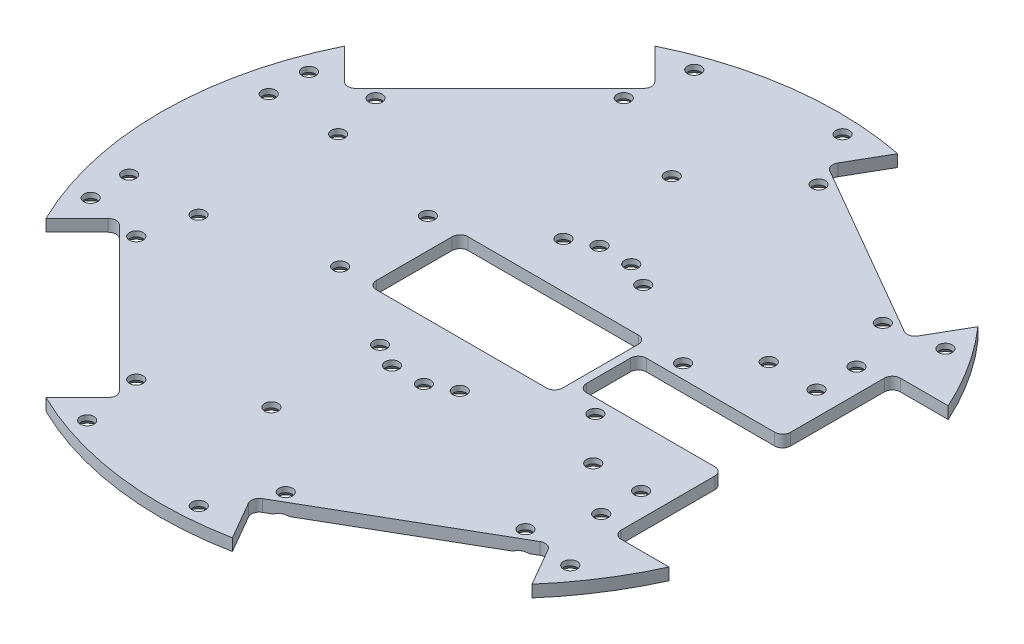
SolidWorks part; units mm, degrees
material "Liga 6061"
ref_plane "Plano frontal" through (0, 0, 0) normal (0, 0, 1) x (1, 0, 0)
ref_plane "Plano superior" through (0, 0, 0) normal (0, 1, 0) x (1, 0, 0)
ref_plane "Plano direito" through (0, 0, 0) normal (1, 0, 0) x (0, 0, -1)
sketch "Esboço1" plane through (0, 0, 0) normal (0, 1, 0) x (1, 0, 0)
  line L0 (0, -20.0389) -> (0, 0) construction
  line L1 (0, 0) -> (-50000, 0) construction
  line L2 (0, 0) -> (-35355.3391, -35355.3391) construction
  line L3 (-76.317, -37.4261) -> (-37.4261, -76.317) construction
  line L4 (16.3986, -83.4032) -> (64.03, -55.9032) construction
  line L5 (0, 0) -> (25000, -43301.2702) construction
  line L6 (16.3986, 83.4032) -> (64.03, 55.9032) construction
  line L7 (-76.317, 37.4261) -> (-37.4261, 76.317) construction
  line L8 (-61.1142, -30.0015) -> (-30.0015, -61.1142) construction
  line L9 (13.1617, -66.7968) -> (51.2668, -44.7968) construction
  line L10 (-67.1246, -28.2337) -> (-28.2337, -67.1246)
  line L15 (-67.1246, -28.2337) -> (-76.317, -37.4261)
  line L16 (-28.2337, -67.1246) -> (-37.4261, -76.317)
  line L17 (9.8986, -72.1448) -> (57.53, -44.6448)
  line L18 (64.03, -55.9032) -> (57.53, -44.6448)
  line L19 (16.3986, -83.4032) -> (9.8986, -72.1448)
  line L20 (64.03, 55.9032) -> (57.53, 44.6448)
  line L21 (9.8986, 72.1448) -> (57.53, 44.6448)
  line L22 (16.3986, 83.4032) -> (9.8986, 72.1448)
  line L23 (-28.2337, 67.1246) -> (-37.4261, 76.317)
  line L24 (-67.1246, 28.2337) -> (-28.2337, 67.1246)
  line L25 (-67.1246, 28.2337) -> (-76.317, 37.4261)
  line L28 (0, 0) -> (-75.1754, 27.3616) construction
  line L29 (-9.6973, 69) -> (0, 0) construction
  line L31 (0, 0) -> (64.7214, 47.0228) construction
  line L32 (3, 127.8652) -> (3, -125.0226) construction
  line L34 (0, 85) -> (0, 66.7968) construction
  arc A0 (-37.4261, -76.317) -> (16.3986, -83.4032) centre (0, 0) ccw
  arc A1 (64.03, -55.9032) -> (64.03, 55.9032) centre (0, 0) ccw
  arc A2 (-76.317, 37.4261) -> (-76.317, -37.4261) centre (0, 0) ccw
  arc A3 (16.3986, 83.4032) -> (-37.4261, 76.317) centre (0, 0) ccw
  circle A4 centre (-61.1142, -30.0015) radius 1.7
  circle A5 centre (-30.0015, -61.1142) radius 1.7
  circle A6 centre (13.1617, -66.7968) radius 1.7
  circle A7 centre (51.2668, -44.7968) radius 1.7
  circle A8 centre (-61.1142, 30.0015) radius 1.7
  circle A9 centre (-30.0015, 61.1142) radius 1.7
  circle A10 centre (13.1617, 66.7968) radius 1.7
  circle A11 centre (51.2668, 44.7968) radius 1.7
  circle A14 centre (-75.3985, 17.5) radius 1.5
  circle A15 centre (-58, 17.5) radius 1.5
  circle A16 centre (-58, -17.5) radius 1.5
  circle A17 centre (-75.3985, -17.5) radius 1.5
  circle A24 centre (-27.3176, 76.108) radius 1.5
  circle A32 centre (-75.1754, 27.3616) radius 1.5
  circle A33 centre (64.7214, 47.0228) radius 1.5
  circle A34 centre (64.7214, -47.0228) radius 1.5
  circle A35 centre (-75.1754, -27.3616) radius 1.5
  circle A36 centre (7, -26) radius 1.5
  circle A37 centre (13, -23) radius 1.5
  circle A38 centre (35, -11) radius 1.5
  circle A48 centre (5.2686, 80.7056) radius 1.5
  circle A49 centre (-7.0429, 50.1863) radius 1.5
  circle A50 centre (-27.3176, -76.108) radius 1.5
  circle A51 centre (5.2686, -80.7056) radius 1.5
  circle A52 centre (-7.0429, -50.1863) radius 1.5
  circle A53 centre (-29, -11) radius 1.5
  circle A54 centre (-7, -23) radius 1.5
  circle A55 centre (-1, -26) radius 1.5
  circle A56 centre (35, 11) radius 1.5
  circle A57 centre (13, 23) radius 1.5
  circle A58 centre (7, 26) radius 1.5
  circle A59 centre (-1, 26) radius 1.5
  circle A60 centre (-7, 23) radius 1.5
  circle A61 centre (-29, 11) radius 1.5
  point P6 (0, 0)
  point P13 (-56.8716, -56.8716)
  point P14 (51.2668, 44.7968)
  point P17 (40.2143, -69.6532)
  point P21 (-45.5579, -45.5579)
  point P24 (32.2143, -55.7968)
  point P25 (13.1617, 66.7968)
  point P26 (-30.0015, 61.1142)
  point P27 (-61.1142, 30.0015)
  point P42 (-27.3176, 76.108)
  point P48 (-47.6792, -47.6792)
  point P51 (33.7143, -58.3948)
  point P52 (-71.7208, -32.8299)
  point P57 (-71.7208, 32.8299)
  point P63 (-75.3985, 17.5)
  point P64 (-58, 17.5)
  point P73 (-9.6883, 68.9348)
  point P80 (-9.6973, 69)
  point P113 (-9.6973, 69)
  dimension "D1" = 170
  dimension "D6" = 3.4
  dimension "D12" = 7
  dimension "D17" = 3
  dimension "D18" = 3
  dimension "D11" = 3
  dimension "D14" = 58
  dimension "D10" = 3
  dimension "D22" = 3
  dimension "D23" = 3
  dimension "D24" = 3
  dimension "D25" = 3
  dimension "D26" = 3
  dimension "D29" = 26
  dimension "D30" = 4
  dimension "D31" = 10
  dimension "D32" = 32
  dimension "D2" = 45
  dimension "D3" = 55
  dimension "D4" = 30
  dimension "D5" = 44
  dimension "D7" = 69
  dimension "D8" = 82
  dimension "D9" = 19
  dimension "D13" = 17.3985
  dimension "D15" = 20
  dimension "D16" = 17.5
  dimension "D19" = 36
  dimension "D20" = 80
  dimension "D21" = 80
  dimension "D27" = 11
  dimension "D28" = 23
  dimension "D33" = 3
extrude "Base" add sketch "Esboço1" along normal blind 3
sketch "Esboço21" plane through (0, 0, 0) normal (0, -1, 0) x (1, 0, 0)
  line L0 (0, 0) -> (50000, 0) construction
  line L2 (63.4597, -35) -> (77.4597, -35)
  line L3 (63.4597, -35) -> (63.4597, 35)
  line L4 (63.4597, 35) -> (77.4597, 35)
  line L6 (63.4597, -35) -> (77.4597, 35) construction
  line L7 (63.4597, 35) -> (77.4597, -35) construction
  arc A0 (77.4597, 35) -> (77.4597, -35) centre (0, 0) cw
  circle A1 centre (57.4597, 32) radius 1.5
  circle A2 centre (57.4597, 22) radius 1.5
  circle A3 centre (45.4597, 22) radius 1.5
  circle A4 centre (45.4597, -22) radius 1.5
  circle A5 centre (57.4597, -22) radius 1.5
  circle A6 centre (57.4597, -32) radius 1.5
  point P3 (70.4597, 0)
  point P9 (57.4597, 32)
  point P10 (57.4597, 22)
  point P11 (45.4597, 22)
  dimension "D8" = 3
  dimension "D9" = 3
  dimension "D10" = 3
  dimension "D1" = 70
  dimension "D2" = 14
  dimension "D3" = 85
  dimension "D4" = 3
  dimension "D5" = 10
  dimension "D6" = 12
  dimension "D7" = 6
extrude "Boca Chute" cut sketch "Esboço21" against normal blind 20
sketch "Esboço32" plane through (63.4597, 0, 0) normal (1, 0, 0) x (0, 0, -1)
  line L0 (0, 7.9765) -> (0, -7.5498) construction
  line L1 (-35, 1.5) -> (35, 1.5) construction
  line L2 (-35, 3) -> (-35, 0) construction
  line L3 (35, 3) -> (35, 0) construction
  line L4 (35, 3) -> (-35, 3) construction
  line L5 (-7.5, 0) -> (7.5, 0)
  line L6 (-7.5, 0) -> (-7.5, 3)
  line L7 (-7.5, 3) -> (7.5, 3)
  line L8 (7.5, 0) -> (7.5, 3)
  line L9 (-7.5, 0) -> (7.5, 3) construction
  line L10 (-7.5, 3) -> (7.5, 0) construction
  point P9 (0, 1.5)
  dimension "D1" = 15
extrude "Corte-extrusão2" cut sketch "Esboço32" against normal blind 36.19
sketch "Esboço33" plane through (0, 3, 0) normal (0, 1, 0) x (1, 0, 0)
  line L0 (57.9822, 0) -> (-158.875, 0) construction
  line L1 (27.2697, 7.5) -> (27.2697, -7.5) construction
  line L2 (-21.4303, -11.5) -> (25.2697, -11.5)
  line L3 (-21.4303, -11.5) -> (-21.4303, 11.5)
  line L4 (-21.4303, 11.5) -> (25.2697, 11.5)
  line L5 (25.2697, -11.5) -> (25.2697, 11.5)
  line L6 (-21.4303, -11.5) -> (25.2697, 11.5) construction
  line L7 (-21.4303, 11.5) -> (25.2697, -11.5) construction
  point P1 (1.9197, 0)
  dimension "D1" = 2
  dimension "D2" = 46.7
  dimension "D3" = 23
extrude "Corte-extrusão3" cut sketch "Esboço33" against normal through all
hole_wizard "Escareado para SFHCS M31" positions "Esboço34" profile "Esboço35" countersink size "M3" standard "Ansi Metric" end condition through all
sketch "Esboço34" plane through (0, 0, 0) normal (0, -1, 0) x (-1, 0, 0)
  point P0 (-64.7214, 47.0228)
  point P3 (-57.4597, 32)
  point P6 (-57.4597, 22)
  point P9 (-51.2668, 44.7968)
  point P12 (-45.4597, 22)
  point P15 (-35, 11)
  point P18 (-13.1617, 66.7968)
  point P21 (-5.2686, 80.7056)
  point P24 (7.0429, 50.1863)
  point P27 (1, 26)
  point P30 (-7, 26)
  point P33 (-13, 23)
  point P36 (7, 23)
  point P39 (7.0429, 50.1863)
  point P41 (27.3176, 76.108)
  point P44 (30.0015, 61.1142)
  point P47 (29, 11)
  point P50 (61.1142, 30.0015)
  point P53 (58, 17.5)
  point P56 (75.3985, 17.5)
  point P59 (75.1754, 27.3616)
  point P62 (-35, -11)
  point P65 (-45.4597, -22)
  point P68 (-57.4597, -22)
  point P71 (-57.4597, -32)
  point P74 (-64.7214, -47.0228)
  point P77 (-51.2668, -44.7968)
  point P80 (-13.1617, -66.7968)
  point P83 (-5.2686, -80.7056)
  point P86 (7.0429, -50.1863)
  point P89 (-13, -23)
  point P92 (-7, -26)
  point P95 (1, -26)
  point P98 (7, -23)
  point P101 (30.0015, -61.1142)
  point P104 (27.3176, -76.108)
  point P107 (29, -11)
  point P110 (58, -17.5)
  point P113 (75.3985, -17.5)
  point P116 (75.1754, -27.3616)
  point P119 (61.1142, -30.0015)
sketch "Esboço35" plane through (64.7214, 0, -47.0228) normal (1, 0, 0) x (0, 0, -1)
  line L0 (0, 0) -> (0, 3)
  line L1 (0, 3) -> (1.7, 3)
  line L2 (1.7, 3) -> (1.7, 1.66)
  line L3 (1.7, 1.66) -> (3.36, 0)
  line L5 (3.36, 0) -> (0, 0)
  line L6 (-1.7, 1.66) -> (-3.36, 0) construction
  line L11 (0, -6.35) -> (0, 107.95) construction
  dimension "Thru Hole Dia." = 3.4
  dimension "Thru Hole Depth" = 3
  dimension "Near C'Sink Dia." = 6.72
  dimension "Near C'Sink Angle" = 90
fillet "Filete1" radius 2 18 edges at (25.2697, 1.5, 11.5) (25.2697, 1.5, -11.5) (-21.4303, 1.5, -11.5) (-21.4303, 1.5, 11.5) (63.4597, 1.5, 35) (63.4597, 1.5, -35) (63.4597, 1.5, 7.5) (63.4597, 1.5, -7.5) (27.2697, 1.5, 7.5) (27.2697, 1.5, -7.5) (9.8986, 1.5, -72.1448) (57.53, 1.5, -44.6448) (-67.1246, 1.5, -28.2337) (-28.2337, 1.5, -67.1246) (-67.1246, 1.5, 28.2337) (-28.2337, 1.5, 67.1246) (9.8986, 1.5, 72.1448) (57.53, 1.5, 44.6448)
